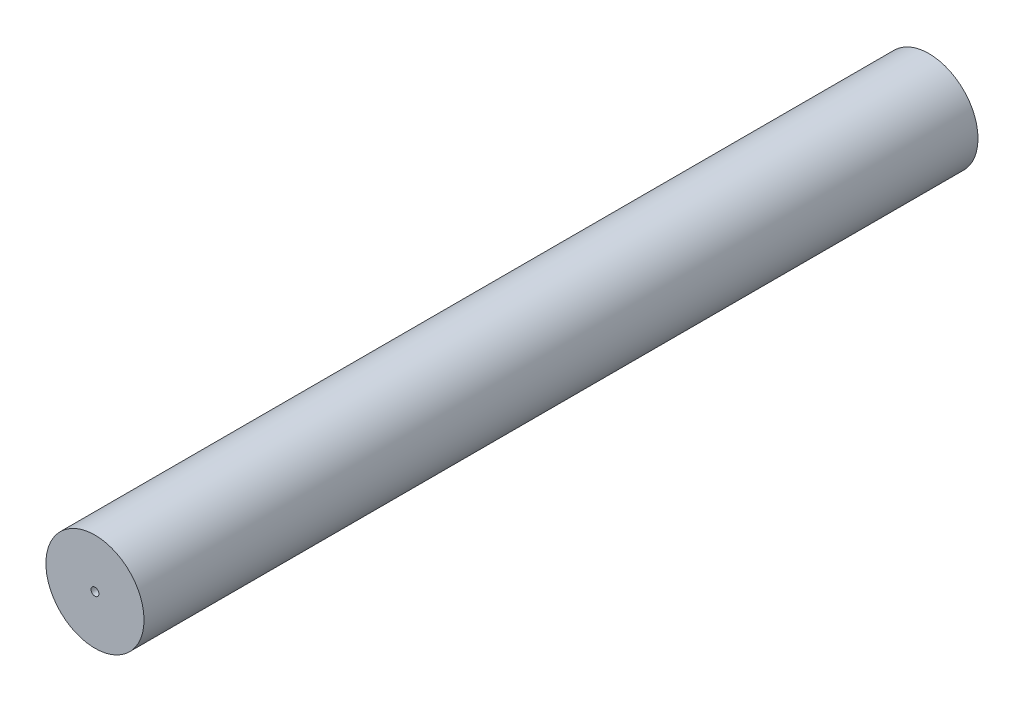
SolidWorks part; units mm, degrees
ref_plane "Front Plane" through (0, 0, 0) normal (0, 0, 1) x (1, 0, 0)
ref_plane "Top Plane" through (0, 0, 0) normal (0, 1, 0) x (1, 0, 0)
ref_plane "Right Plane" through (0, 0, 0) normal (1, 0, 0) x (0, 0, -1)
sketch "Sketch1" plane through (0, 0, 0) normal (0, 0, 1) x (1, 0, 0)
  circle A0 centre (0, 0) radius 5
  dimension "D1" = 10
extrude "Boss-Extrude1" add sketch "Sketch1" along normal blind 85
sketch "Sketch3" plane through (0, 0, 85) normal (0, 0, 1) x (1, 0, 0)
  circle A0 centre (0, 0) radius 0.4
  dimension "D1" = 0.8
extrude "Cut-Extrude2" cut sketch "Sketch3" against normal through all
